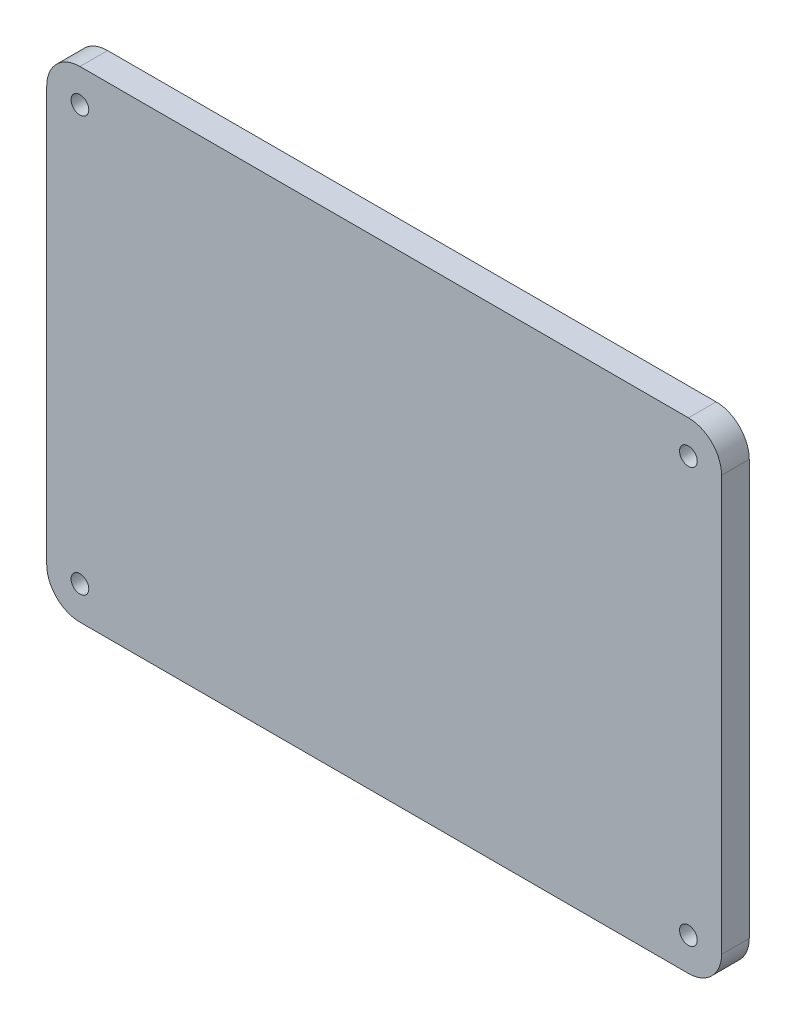
SolidWorks part; units mm, degrees
ref_plane "Front" through (0, 0, 0) normal (0, 0, 1) x (1, 0, 0)
ref_plane "Top" through (0, 0, 0) normal (0, 1, 0) x (1, 0, 0)
ref_plane "Right" through (0, 0, 0) normal (1, 0, 0) x (0, 0, -1)
sketch "Эскиз1" plane through (0, 0, 0) normal (0, 0, 1) x (1, 0, 0)
  line L0 (130, -14) -> (20, -14)
  line L1 (136, -8) -> (136, 67)
  line L2 (130, 73) -> (20, 73)
  line L3 (14, -8) -> (14, 67)
  circle A4 centre (130, 67) radius 1.6
  circle A5 centre (20, 67) radius 1.6
  circle A6 centre (20, -8) radius 1.6
  circle A7 centre (130, -8) radius 1.6
  arc A8 (130, -14) -> (136, -8) centre (130, -8) ccw
  arc A9 (14, -8) -> (20, -14) centre (20, -8) ccw
  arc A10 (20, 73) -> (14, 67) centre (20, 67) ccw
  arc A11 (136, 67) -> (130, 73) centre (130, 67) ccw
  dimension "D1" = 2
  dimension "D2" = 2
extrude "Бобышка-Вытянуть1" add sketch "Эскиз1" along normal blind 5
